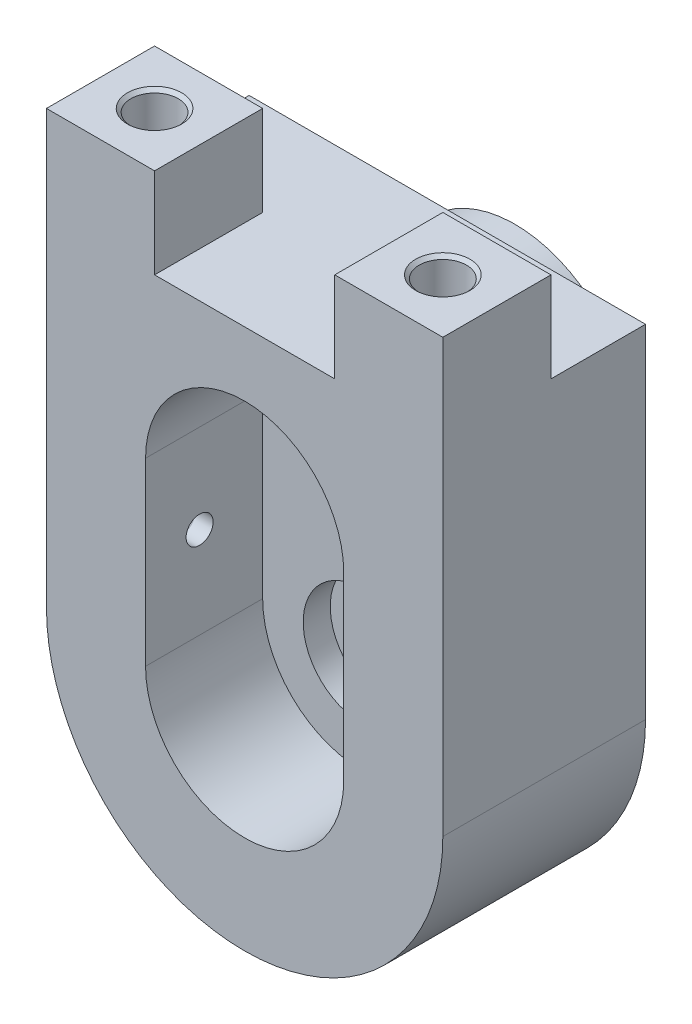
SolidWorks part; units mm, degrees
ref_plane "정면" through (0, 0, 0) normal (0, 0, 1) x (1, 0, 0)
ref_plane "윗면" through (0, 0, 0) normal (0, 1, 0) x (1, 0, 0)
ref_plane "우측면" through (0, 0, 0) normal (1, 0, 0) x (0, 0, -1)
sketch "스케치1" plane through (0, 0, 0) normal (0, 0, 1) x (1, 0, 0)
  line L0 (5.4763, 36.2605) -> (20, 36.2605)
  line L1 (20, 36.2605) -> (20, 56.2605)
  line L2 (20, 56.2605) -> (44, 56.2605)
  line L3 (44, 56.2605) -> (44, -39.7395)
  line L4 (-44, -39.7395) -> (-44, 56.2605)
  line L5 (-44, 56.2605) -> (-20, 56.2605)
  line L6 (-20, 56.2605) -> (-20, 36.2605)
  line L7 (-20, 36.2605) -> (5.4763, 36.2605)
  arc A0 (44, -39.7395) -> (-44, -39.7395) centre (0, -39.7395) cw
  point P9 (0, -83.7395)
  point P11 (0, 0)
  dimension "D1" = 24
  dimension "D2" = 140
  dimension "D3" = 20
  dimension "D4" = 88
extrude "보스-돌출1" add sketch "스케치1" along normal blind 45
sketch "스케치3" plane through (0, 0, 45) normal (0, 0, 1) x (1, 0, 0)
  line L0 (0, 0) -> (0, -40) construction
  line L1 (22, 0) -> (22, -40)
  line L2 (-22, 0) -> (-22, -40)
  arc A0 (22, 0) -> (-22, 0) centre (0, 0) ccw
  arc A1 (-22, -40) -> (22, -40) centre (0, -40) ccw
  point P3 (0, -20)
  point P8 (0, -62)
  dimension "D1" = 22
  dimension "D2" = 62
extrude "컷-돌출1" cut sketch "스케치3" against normal blind 26 contours L1 A1 L2 A0
sketch "스케치4" plane through (0, 0, 19) normal (0, 0, 1) x (1, 0, 0)
  circle A0 centre (0, 0) radius 13
  circle A1 centre (0, -40) radius 13
  dimension "D1" = 26
  dimension "D2" = 26
extrude "컷-돌출2" cut sketch "스케치4" against normal through all contours A0
sketch "스케치5" plane through (0, 0, 19) normal (0, 0, 1) x (1, 0, 0)
  circle A0 centre (0, -40) radius 13
  dimension "D1" = 26
extrude "컷-돌출3" cut sketch "스케치5" against normal blind 6
ref_plane "평면2" through (45, 0, 0) normal (1, 0, 0) x (0, 0, -1)
sketch "스케치7" plane through (45, 0, 0) normal (1, 0, 0) x (0, 0, -1)
  line L1 (-21, 84.7904) -> (24.2026, 84.7904)
  line L2 (-21, 84.7904) -> (-21, 36.2605)
  line L3 (-21, 36.2605) -> (24.2026, 36.2605)
  line L4 (24.2026, 84.7904) -> (24.2026, 36.2605)
  dimension "D1" = 24
  dimension "D2" = 20
extrude "컷-돌출4" cut sketch "스케치7" against normal through all
sketch "스케치8" plane through (0, 0, 0) normal (0, 0, -1) x (-1, 0, 0)
  circle A0 centre (0, 0) radius 26
  circle A1 centre (0, 0) radius 11
  dimension "D1" = 52
  dimension "D2" = 22
extrude "보스-돌출3" add sketch "스케치8" along normal blind 15
sketch "스케치12" plane through (0, 56.2605, 0) normal (0, 1, 0) x (1, 0, 0)
  point P12 (32, -33)
hole_wizard "M12x1.5 나사 구멍3" positions "3D스케치8" profile "스케치13" tap size "M12x1.5" standard "KS"
sketch3d "3D스케치8"
  point P0 (32, 56.2605, 33)
sketch "스케치13" plane through (32, 56.2605, 33) normal (1, 0, 0) x (0, 0, 1)
  line L0 (0, 0) -> (0, 21.1545)
  line L1 (0, 21.1545) -> (5.25, 18)
  line L2 (5.25, 18) -> (5.25, 0.7484)
  line L3 (5.25, 0.7484) -> (6.025, 0)
  line L5 (6.025, 0) -> (0, 0)
  line L6 (-5.25, 0.7484) -> (-6.025, 0) construction
  line L10 (0, 21.1545) -> (-5.25, 18) construction
  line L11 (0, -6.35) -> (0, 107.95) construction
  dimension "탭 드릴 지름" = 10.5
  dimension "탭 드릴 깊이" = 18
  dimension "표면 카운터싱크 지름" = 12.05
  dimension "표면 카운터싱크 각도" = 92
  dimension "드릴 각도" = 118
cosmetic thread "구멍 나사산1" parameters "D1"=15, "D2"=12
ref_plane "평면4" through (0, 0, 0) normal (1, 0, 0) x (0, 0, -1)
mirror "대칭 복사1" about plane through (0, 0, 0) normal (1, 0, 0) of "M12x1.5 나사 구멍3"
cosmetic thread "구멍 나사산2" parameters "D1"=15, "D2"=12
sketch "스케치14" plane through (0, 0, 0) normal (0, 0, -1) x (-1, 0, 0)
  circle A0 centre (0, -40) radius 13 construction
  point P0 (0, 29)
  point P1 (0, -72)
  dimension "D1" = 29
  dimension "D2" = 32
hole_wizard "M5 나사 구멍1" positions "3D스케치9" profile "스케치15" tap size "M5" standard "KS"
sketch3d "3D스케치9"
  point P0 (0, 29, 0)
  point P3 (0, -72, 0)
sketch "스케치15" plane through (0, 29, 0) normal (1, 0, 0) x (0, 1, 0)
  line L0 (0, 0) -> (0, 13.2618)
  line L1 (0, 13.2618) -> (2.1, 12)
  line L2 (2.1, 12) -> (2.1, 0.4104)
  line L3 (2.1, 0.4104) -> (2.525, 0)
  line L5 (2.525, 0) -> (0, 0)
  line L6 (-2.1, 0.4104) -> (-2.525, 0) construction
  line L10 (0, 13.2618) -> (-2.1, 12) construction
  line L11 (0, -6.35) -> (0, 107.95) construction
  dimension "탭 드릴 지름" = 4.2
  dimension "탭 드릴 깊이" = 12
  dimension "표면 카운터싱크 지름" = 5.05
  dimension "표면 카운터싱크 각도" = 92
  dimension "드릴 각도" = 118
cosmetic thread "구멍 나사산3" parameters "D1"=10, "D2"=5
cosmetic thread "구멍 나사산4" parameters "D1"=10, "D2"=5
ref_plane "평면5" through (0, 0, 33) normal (0, 0, 1) x (1, 0, 0)
sketch "스케치16" plane through (0, 0, 33) normal (0, 0, 1) x (1, 0, 0)
  line L0 (-32, 56.2605) -> (-32, -13.7395)
  line L1 (-20, 56.2605) -> (-44, 56.2605) construction
  line L2 (-26, -19.7395) -> (-16.9264, -19.7395)
  arc A0 (-32, -13.7395) -> (-26, -19.7395) centre (-26, -13.7395) ccw
  point P7 (0, 0)
  dimension "D1" = 6
  dimension "D2" = 76
ref_plane "평면6" through (-32, 56.2605, 33) normal (0, -1, 0) x (-1, 0, 0)
sketch "스케치17" plane through (-32, 56.2605, 33) normal (0, -1, 0) x (-1, 0, 0)
  circle A0 centre (0, 0) radius 3
  dimension "D1" = 6
sweep "컷-스윕1" cut profiles "스케치17" path "스케치16"
ref_plane "평면8" through (0, 0, 0) normal (1, 0, 0) x (0, 0, -1)
mirror "대칭 복사3" about plane through (0, 0, 0) normal (1, 0, 0) of "컷-스윕1"
